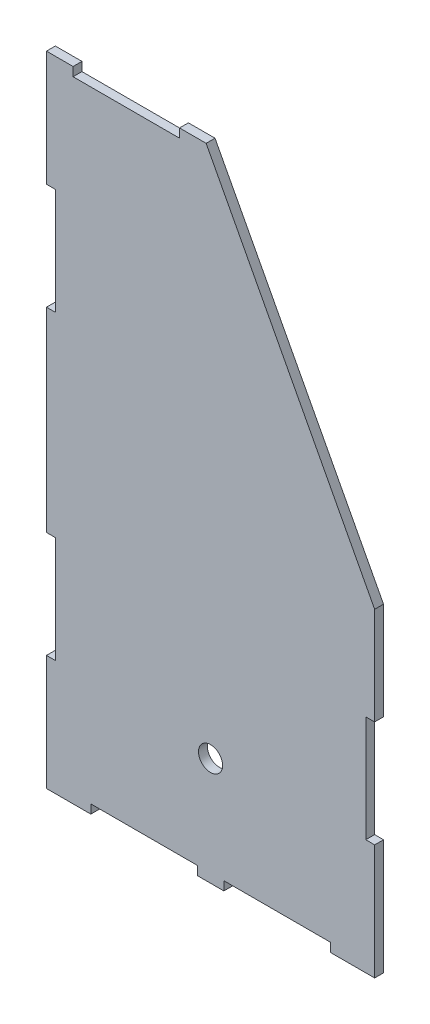
SolidWorks part; units mm, degrees
ref_plane "Front Plane" through (0, 0, 0) normal (0, 0, 1) x (1, 0, 0)
ref_plane "Top Plane" through (0, 0, 0) normal (0, 1, 0) x (1, 0, 0)
ref_plane "Right Plane" through (0, 0, 0) normal (1, 0, 0) x (0, 0, -1)
sketch "Sketch1" plane through (0, 0, 0) normal (0, 0, 1) x (1, 0, 0)
  line L0 (435.5199, 642.8699) -> (556.1699, 414.2699)
  line L1 (321.2199, 642.8699) -> (435.5199, 642.8699)
  line L2 (321.2199, 642.8699) -> (321.2199, 185.6699)
  line L3 (321.2199, 185.6699) -> (556.1699, 185.6699)
  line L4 (556.1699, 414.2699) -> (556.1699, 185.6699)
  dimension "D1" = 234.95
  dimension "D2" = 457.2
  dimension "D3" = 114.3
  dimension "D4" = 228.6
extrude "Boss-Extrude3" add sketch "Sketch1" along normal blind 6.35
sketch "Sketch2" plane through (0, 0, 6.35) normal (0, 0, 1) x (1, 0, 0)
  line L0 (327.5699, 642.8699) -> (327.5699, 185.6699) construction
  line L1 (435.5199, 642.8699) -> (321.2199, 642.8699) construction
  line L2 (321.2199, 185.6699) -> (556.1699, 185.6699) construction
  line L3 (321.2199, 192.0199) -> (556.1699, 192.0199) construction
  line L4 (321.2199, 642.8699) -> (321.2199, 185.6699) construction
  line L5 (556.1699, 185.6699) -> (556.1699, 414.2699) construction
  line L6 (321.2199, 636.5199) -> (438.8713, 636.5199) construction
  line L7 (549.8199, 185.6699) -> (549.8199, 426.3014) construction
  line L8 (556.1699, 414.2699) -> (435.5199, 642.8699) construction
  line L10 (416.4699, 642.8699) -> (340.2699, 642.8699)
  line L11 (416.4699, 642.8699) -> (416.4699, 636.5199)
  line L12 (416.4699, 636.5199) -> (340.2699, 636.5199)
  line L13 (340.2699, 642.8699) -> (340.2699, 636.5199)
  line L14 (321.2199, 560.3199) -> (327.5699, 560.3199)
  line L15 (321.2199, 560.3199) -> (321.2199, 484.1199)
  line L16 (321.2199, 484.1199) -> (327.5699, 484.1199)
  line L17 (327.5699, 560.3199) -> (327.5699, 484.1199)
  line L18 (321.2199, 344.4199) -> (327.5699, 344.4199)
  line L19 (321.2199, 344.4199) -> (321.2199, 268.2199)
  line L20 (321.2199, 268.2199) -> (327.5699, 268.2199)
  line L21 (327.5699, 344.4199) -> (327.5699, 268.2199)
  line L22 (352.9699, 192.0199) -> (429.1699, 192.0199)
  line L23 (352.9699, 192.0199) -> (352.9699, 185.6699)
  line L24 (352.9699, 185.6699) -> (429.1699, 185.6699)
  line L25 (429.1699, 192.0199) -> (429.1699, 185.6699)
  line L26 (448.2199, 192.0199) -> (524.4199, 192.0199)
  line L27 (448.2199, 192.0199) -> (448.2199, 185.6699)
  line L28 (448.2199, 185.6699) -> (524.4199, 185.6699)
  line L29 (524.4199, 192.0199) -> (524.4199, 185.6699)
  line L30 (549.8199, 344.4199) -> (556.1699, 344.4199)
  line L31 (549.8199, 344.4199) -> (549.8199, 268.2199)
  line L32 (549.8199, 268.2199) -> (556.1699, 268.2199)
  line L33 (556.1699, 344.4199) -> (556.1699, 268.2199)
  point P38 (552.9949, 268.2199)
  dimension "D1" = 6.35
  dimension "D2" = 6.35
  dimension "D3" = 6.35
  dimension "D4" = 6.35
  dimension "D6" = 76.2
  dimension "D8" = 82.55
  dimension "D9" = 82.55
  dimension "D5" = 19.05
  dimension "D10" = 76.2
  dimension "D11" = 76.2
  dimension "D12" = 19.05
  dimension "D14" = 82.55
  dimension "D7" = 76.2
  dimension "D13" = 31.75
extrude "Cut-Extrude1" cut sketch "Sketch2" against normal through all
sketch "Sketch3" plane through (0, 0, 0) normal (0, 0, 1) x (1, 0, 0)
  line L0 (429.1699, 185.6699) -> (448.2199, 185.6699) construction
  line L1 (556.1699, 185.6699) -> (556.1699, 268.2199) construction
  circle A0 centre (438.6949, 262.9891) radius 8.636
  point P4 (0, 0)
  dimension "D3" = 17.272
  dimension "D1" = 77.3192
  dimension "D2" = 117.475
extrude "Cut-Extrude3" cut sketch "Sketch3" against normal through all and the other way through all
equation "\"width\"= 9in"
equation "\"Height\"= 18in"
equation "\"D3@Sketch1\"=\"width\"/2"
equation "\"D4@Sketch1\"=\"Height\"/2"
equation "\"thick\"= 0.25"
equation "\"D1@Sketch2\"=\"thick\""
equation "\"D2@Sketch2\"=\"thick\""
equation "\"D3@Sketch2\"=\"thick\""
equation "\"D4@Sketch2\"=\"thick\""
equation "\"D2@Sketch1\"=\"Height\""
equation "\"D1@Sketch1\"= \"width\" + \"thick\""
